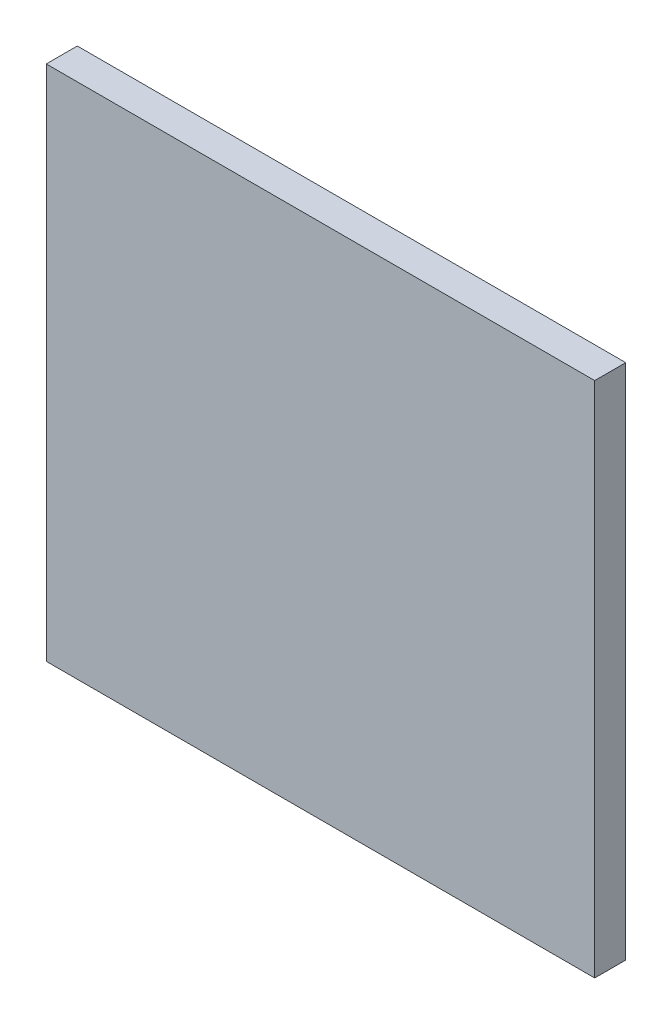
SolidWorks part; units mm, degrees
ref_plane "Front Plane" through (0, 0, 0) normal (0, 0, 1) x (1, 0, 0)
ref_plane "Top Plane" through (0, 0, 0) normal (0, 1, 0) x (1, 0, 0)
ref_plane "Right Plane" through (0, 0, 0) normal (1, 0, 0) x (0, 0, -1)
sketch "Sketch1" plane through (0, 0, 0) normal (0, 0, 1) x (1, 0, 0)
  line L1 (-36.0143, 24.5902) -> (16.9857, 24.5902)
  line L2 (-36.0143, 24.5902) -> (-36.0143, -25.4098)
  line L3 (-36.0143, -25.4098) -> (16.9857, -25.4098)
  line L4 (16.9857, 24.5902) -> (16.9857, -25.4098)
  dimension "D1" = 50
  dimension "D2" = 53
extrude "Boss-Extrude1" add sketch "Sketch1" along normal blind 3
